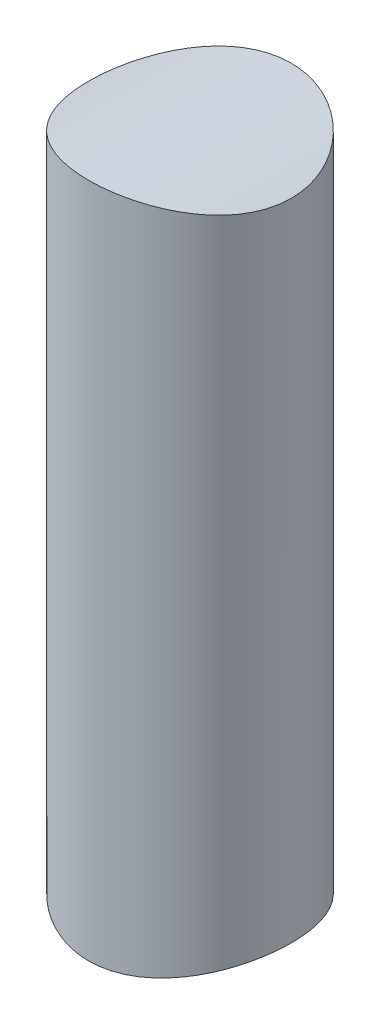
SolidWorks part; units mm, degrees
ref_plane "Alzado" through (0, 0, 0) normal (0, 0, 1) x (1, 0, 0)
ref_plane "Planta" through (0, 0, 0) normal (0, 1, 0) x (1, 0, 0)
ref_plane "Vista lateral" through (0, 0, 0) normal (1, 0, 0) x (0, 0, -1)
sketch "Croquis1" plane through (0, 0, 0) normal (0, 0, 1) x (1, 0, 0)
  circle A0 centre (0, 0) radius 2.5
extrude "Saliente-Extruir1" add sketch "Croquis1" along normal blind 5
sketch "Croquis2" plane through (0, 0, 0) normal (0, 1, 0) x (1, 0, 0)
  circle A0 centre (0, -2.5) radius 0.75
extrude "Cortar-Extruir1" cut sketch "Croquis2" against normal mid plane 5 flip side to cut
